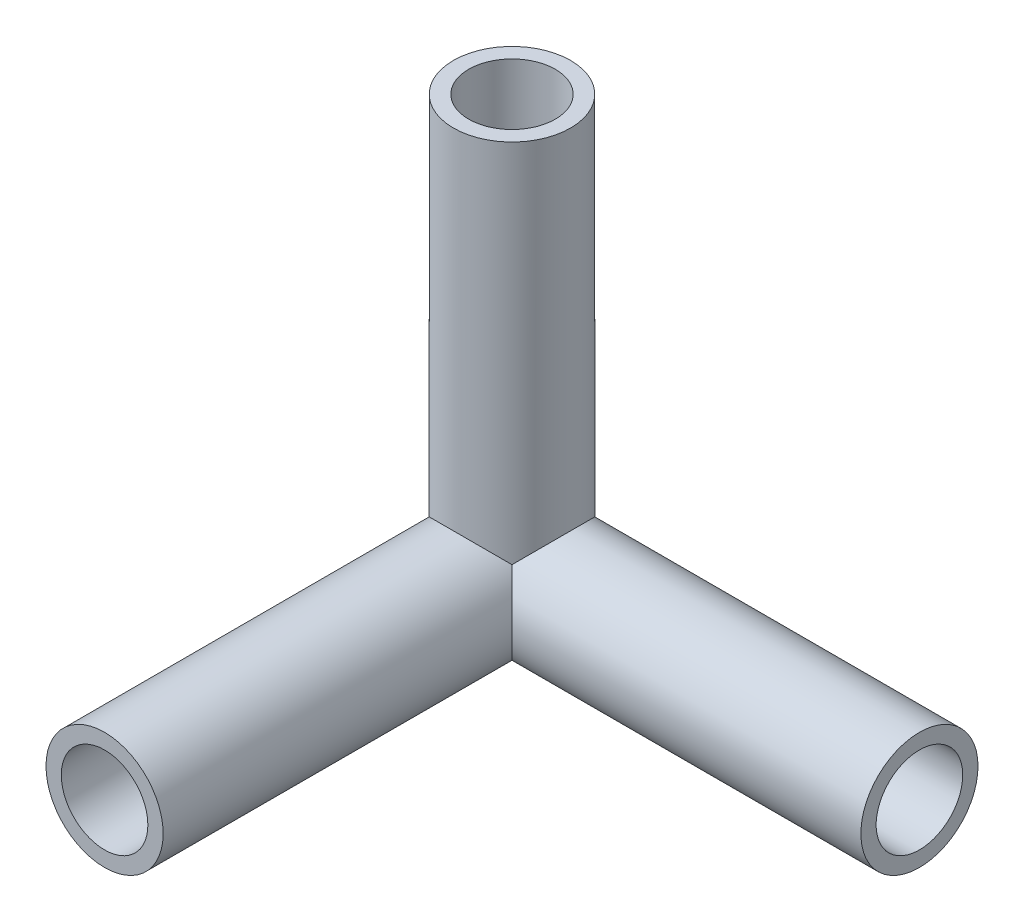
SolidWorks part; units mm, degrees
material "ABS"
ref_plane "前视基准面" through (0, 0, 0) normal (0, 0, 1) x (1, 0, 0)
ref_plane "上视基准面" through (0, 0, 0) normal (0, 1, 0) x (1, 0, 0)
ref_plane "右视基准面" through (0, 0, 0) normal (1, 0, 0) x (0, 0, -1)
sketch "草图1" plane through (0, 0, 0) normal (0, 0, 1) x (1, 0, 0)
  circle A0 centre (0, 0) radius 4.25
  circle A1 centre (0, 0) radius 5.75
  dimension "D1" = 8.5
  dimension "D2" = 1.5
extrude "凸台-拉伸1" add sketch "草图1" along normal blind 40
sketch "草图2" plane through (0, 0, 0) normal (0, 1, 0) x (1, 0, 0)
  circle A0 centre (0, 0) radius 5.75
  circle A1 centre (0, 0) radius 4.25
  dimension "D1" = 8.5
  dimension "D2" = 1.5
extrude "凸台-拉伸2" add sketch "草图2" along normal blind 40
sketch "草图3" plane through (0, 0, 0) normal (1, 0, 0) x (0, 0, -1)
  circle A0 centre (0, 0) radius 4.25
  circle A1 centre (0, 0) radius 5.75
  dimension "D1" = 8.5
extrude "凸台-拉伸3" add sketch "草图3" along normal blind 40
sketch "草图4" plane through (0, 0, 0) normal (0, 0, -1) x (-1, 0, 0)
  line L0 (4.25, 0) -> (5.75, 0)
  line L1 (0, -4.25) -> (0, -5.75)
  line L2 (0, -4.25) -> (0, 0) construction
  arc A0 (0, -4.25) -> (4.25, 0) centre (0, 0) ccw
  arc A1 (0, -4.25) -> (4.25, 0) centre (0, 0) ccw construction
  arc A2 (0, -5.75) -> (5.75, 0) centre (0, 0) ccw
revolve "旋转1" add sketch "草图4" angle 360 about L2
